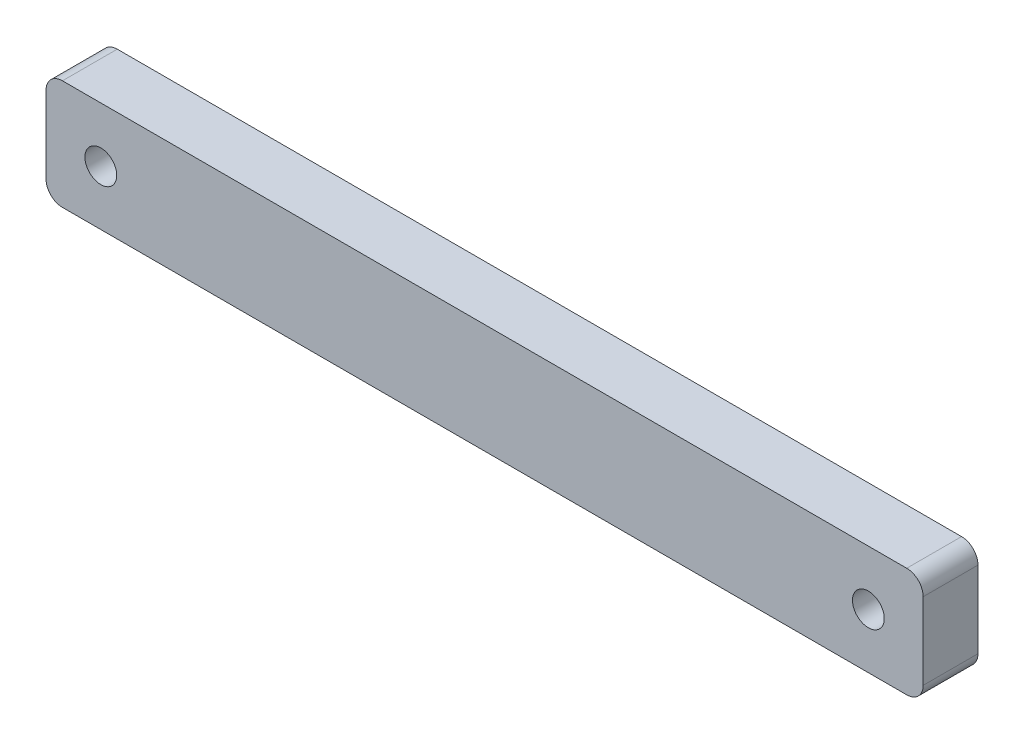
SolidWorks part; units mm, degrees
ref_plane "Front Plane" through (0, 0, 0) normal (0, 0, 1) x (1, 0, 0)
ref_plane "Top Plane" through (0, 0, 0) normal (0, 1, 0) x (1, 0, 0)
ref_plane "Right Plane" through (0, 0, 0) normal (1, 0, 0) x (0, 0, -1)
sketch "Sketch1" plane through (0, 0, 0) normal (0, 0, 1) x (1, 0, 0)
  line L1 (97.79, -12.7) -> (-97.79, -12.7)
  line L2 (101.6, -8.89) -> (101.6, 8.89)
  line L3 (97.79, 12.7) -> (-97.79, 12.7)
  line L4 (-101.6, -8.89) -> (-101.6, 8.89)
  line L5 (101.6, -12.7) -> (-101.6, 12.7) construction
  line L6 (101.6, 12.7) -> (-101.6, -12.7) construction
  arc A0 (101.6, 8.89) -> (97.79, 12.7) centre (97.79, 8.89) ccw
  arc A1 (97.79, -12.7) -> (101.6, -8.89) centre (97.79, -8.89) ccw
  arc A2 (-97.79, -12.7) -> (-101.6, -8.89) centre (-97.79, -8.89) cw
  arc A3 (-97.79, 12.7) -> (-101.6, 8.89) centre (-97.79, 8.89) ccw
  circle A4 centre (-88.9, 0) radius 3.683
  circle A5 centre (88.9, 0) radius 3.683
  point P0 (0, 0)
  dimension "D3" = 3.81
  dimension "D6" = 7.366
  dimension "D7" = 7.366
  dimension "D1" = 25.4
  dimension "D2" = 203.2
  dimension "D4" = 88.9
  dimension "D5" = 88.9
extrude "Boss-Extrude1" add sketch "Sketch1" along normal blind 12.7
sketch "Sketch2" plane through (0, 0, 0) normal (0, 0, -1) x (-1, 0, 0)
  circle A0 centre (-88.9, 0) radius 3.683
  circle A1 centre (88.9, 0) radius 3.683
extrude "Boss-Extrude2" add sketch "Sketch2" against normal blind 6.35
sketch "Sketch3" plane through (0, 0, 12.7) normal (0, 0, 1) x (1, 0, 0)
  line L0 (0, 0) -> (0, 28.8785) construction
  line L1 (0, 0) -> (19.2881, 0) construction
  line L2 (0, 12.7) -> (0, -12.7)
  line L3 (0, -12.7) -> (-97.79, -12.7)
  line L4 (-97.79, 12.7) -> (0, 12.7)
  line L6 (-101.6, 8.89) -> (-101.6, -8.89)
  line L7 (-97.79, -12.7) -> (97.79, -12.7)
  line L8 (101.6, -8.89) -> (101.6, 8.89)
  line L9 (97.79, 12.7) -> (-97.79, 12.7)
  line L10 (-101.6, 8.89) -> (-101.6, -8.89)
  line L11 (-97.79, -12.7) -> (0, -12.7)
  line L13 (0, 12.7) -> (-97.79, 12.7)
  arc A0 (-97.79, -12.7) -> (-101.6, -8.89) centre (-97.79, -8.89) cw
  arc A1 (-101.6, 8.89) -> (-97.79, 12.7) centre (-97.79, 8.89) cw
  circle A3 centre (-88.9, 0) radius 3.683
  circle A4 centre (-88.9, 0) radius 3.683
  arc A8 (-101.6, -8.89) -> (-97.79, -12.7) centre (-97.79, -8.89) ccw
  arc A9 (97.79, -12.7) -> (101.6, -8.89) centre (97.79, -8.89) ccw
  arc A10 (101.6, 8.89) -> (97.79, 12.7) centre (97.79, 8.89) ccw
  arc A11 (-97.79, 12.7) -> (-101.6, 8.89) centre (-97.79, 8.89) ccw
  arc A12 (-101.6, -8.89) -> (-97.79, -12.7) centre (-97.79, -8.89) ccw
  arc A15 (-97.79, 12.7) -> (-101.6, 8.89) centre (-97.79, 8.89) ccw
  dimension "D2" = 0
  dimension "D3" = 0
